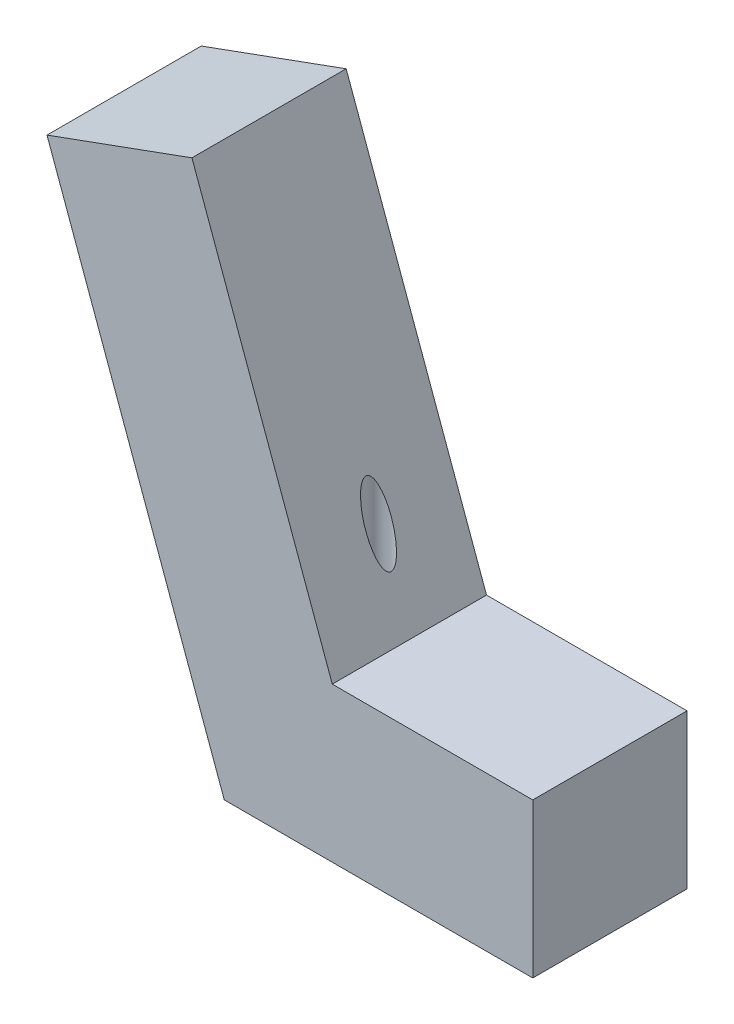
SolidWorks part; units mm, degrees
material "ABS"
ref_plane "Front Plane" through (0, 0, 0) normal (0, 0, 1) x (1, 0, 0)
ref_plane "Top Plane" through (0, 0, 0) normal (0, 1, 0) x (1, 0, 0)
ref_plane "Right Plane" through (0, 0, 0) normal (1, 0, 0) x (0, 0, -1)
sketch "Sketch1" plane through (0, 0, 0) normal (0, 0, 1) x (1, 0, 0)
  line L0 (0, 0) -> (-19.9502, 54.8127)
  line L1 (-19.9502, 54.8127) -> (3.918, 63.5)
  line L2 (3.918, 63.5) -> (27.0301, 0)
  line L3 (27.0301, 0) -> (60.0448, 0)
  line L4 (60.0448, 0) -> (60.0448, -25.4)
  line L5 (60.0448, -25.4) -> (9.2448, -25.4)
  line L6 (9.2448, -25.4) -> (0, 0)
  dimension "D1" = 25.4
  dimension "D2" = 70
  dimension "D3" = 88.9
  dimension "D4" = 50.8
extrude "Boss-Extrude1" add sketch "Sketch1" along normal blind 25.4
sketch "Sketch3" plane through (0, -25.4, 0) normal (0, -1, 0) x (1, 0, 0)
  line L0 (60.0448, 12.7) -> (9.2448, 12.7) construction
  line L1 (60.0448, 25.4) -> (60.0448, 0) construction
  line L2 (9.2448, 25.4) -> (9.2448, 0) construction
  circle A0 centre (21.9448, 12.7) radius 6.35
  point P8 (0, 0)
  dimension "D1" = 12.7
  dimension "D2" = 12.7
extrude "Cut-Extrude1" cut sketch "Sketch3" against normal blind 15.875
sketch "Sketch4" plane through (0, -9.525, 0) normal (0, -1, 0) x (1, 0, 0)
  circle A0 centre (21.9448, 12.7) radius 6.35 construction
  circle A1 centre (21.9448, 12.7) radius 6.35 construction
  circle A2 centre (21.9448, 12.7) radius 2.0955
  dimension "D1" = 4.191
extrude "Cut-Extrude2" cut sketch "Sketch4" against normal through all
